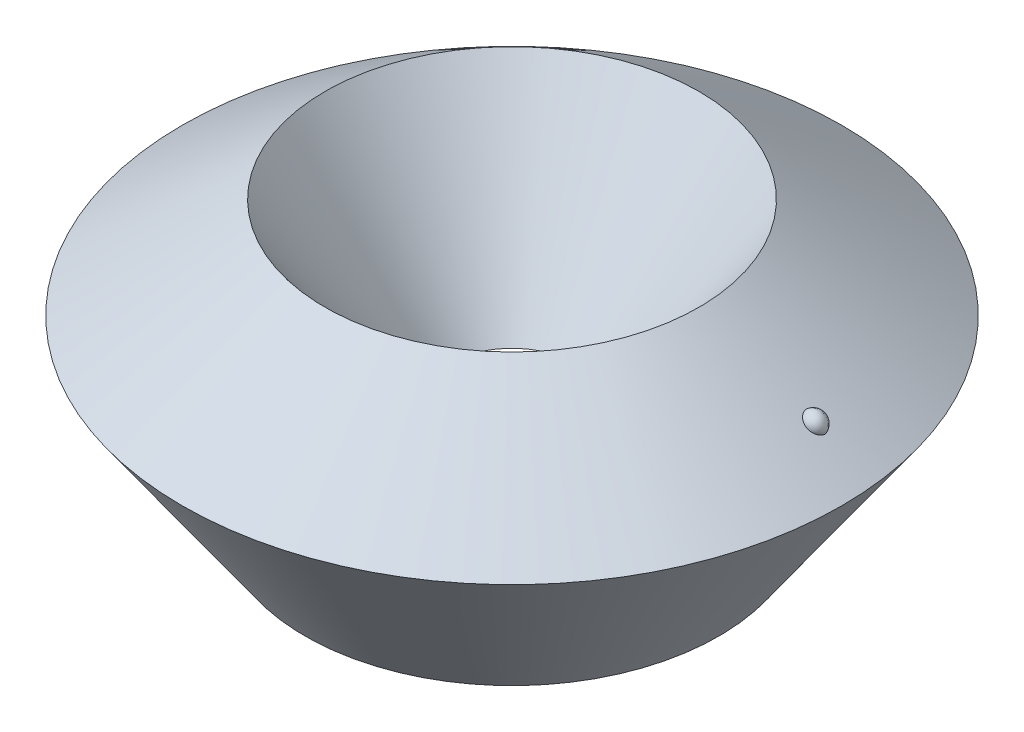
SolidWorks part; units mm, degrees
ref_plane "Front Plane" through (0, 0, 0) normal (0, 0, 1) x (1, 0, 0)
ref_plane "Top Plane" through (0, 0, 0) normal (0, 1, 0) x (1, 0, 0)
ref_plane "Right Plane" through (0, 0, 0) normal (1, 0, 0) x (0, 0, -1)
other "Configuration Table"
sketch "Sketch1" plane through (0, 0, 0) normal (0, 0, 1) x (1, 0, 0)
  line L0 (-692.9817, -274.1632) -> (-1104.5708, 309.8742)
  line L1 (-692.9817, -274.1632) -> (-214.8581, 62.7851)
  line L2 (-1104.5708, 309.8742) -> (-626.4471, 646.8226)
  line L3 (-214.8581, 62.7851) -> (-626.4471, 646.8226)
  line L4 (-692.9817, -274.1632) -> (-626.4471, 646.8226) construction
  line L5 (-1104.5708, 309.8742) -> (-214.8581, 62.7851) construction
  line L6 (0, 0) -> (0, 1167.3325) construction
  point P6 (-659.7144, 186.3297)
revolve "Revolve1" add sketch "Sketch1" angle 360 about L6
ref_plane "Plane1" through (0, 0, 0) normal (0.0872, 0, 0.9962) x (0, 1, 0)
sketch "Sketch3" plane through (0, 0, 0) normal (0.0872, 0, 0.9962) x (0.9962, 0, -0.0872)
  line L0 (626.4471, 646.8226) -> (1104.5708, 309.8742) construction
  line L1 (968.5453, 405.7355) -> (907.1297, 449.0169)
  arc A0 (968.5453, 405.7355) -> (907.1297, 449.0169) centre (934.1796, 422.1857) ccw
  dimension "D2" = 38.1
  dimension "D1" = 381
  dimension "D3" = 6.35
revolve "Revolve2" add sketch "Sketch3" angle 360 about L0
